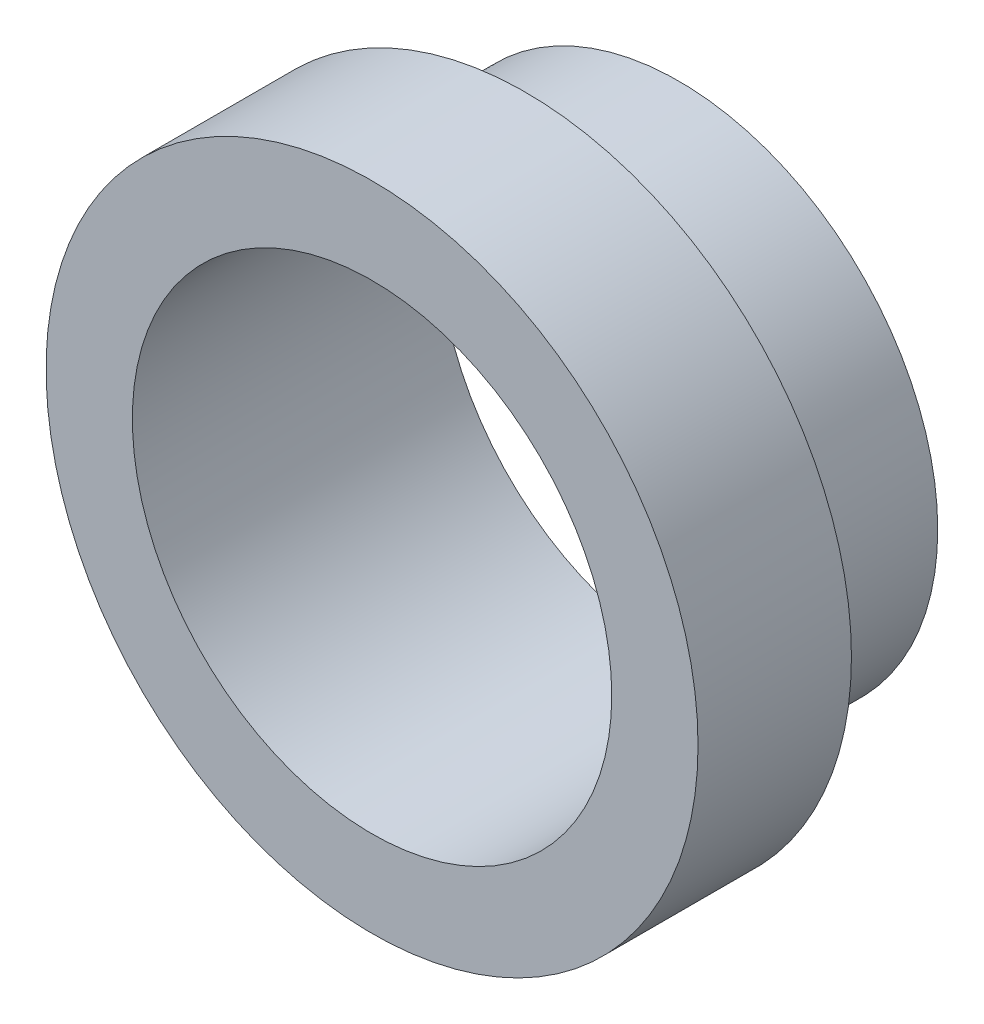
SolidWorks part; units mm, degrees
ref_plane "Спереди" through (0, 0, 0) normal (0, 0, 1) x (1, 0, 0)
ref_plane "Сверху" through (0, 0, 0) normal (0, 1, 0) x (1, 0, 0)
ref_plane "Справа" through (0, 0, 0) normal (1, 0, 0) x (0, 0, -1)
sketch "Эскиз1" plane through (0, 0, 0) normal (0, 0, 1) x (1, 0, 0)
  circle A0 centre (0, 0) radius 13.5
  circle A1 centre (0, 0) radius 12.5
extrude "Needle_neck" add sketch "Эскиз1" along normal blind 8 from offset 47.5
sketch "Эскиз2" plane through (0, 0, 0) normal (0, 0, 1) x (1, 0, 0)
  circle A0 centre (0, 0) radius 17
  circle A1 centre (0, 0) radius 12.5
extrude "Needle_outer_hub" add sketch "Эскиз2" along normal blind 8 from offset 55.5
